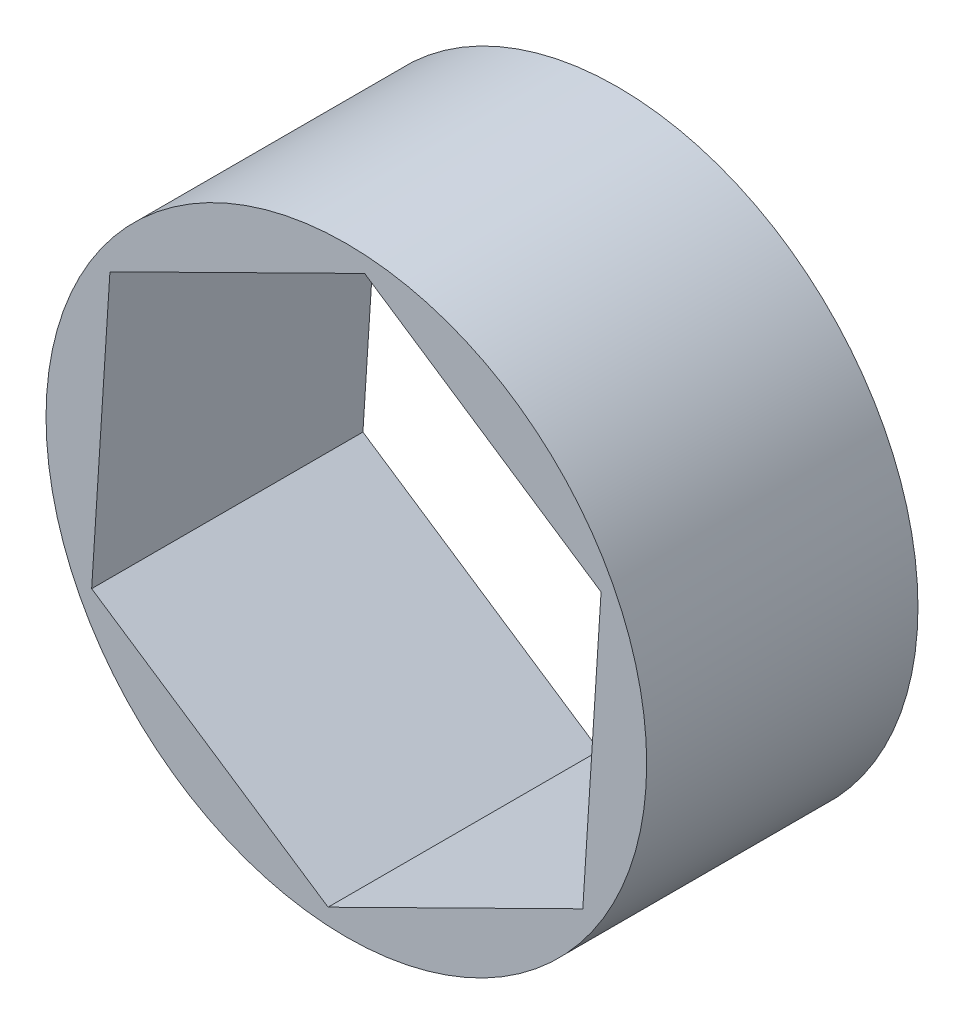
SolidWorks part; units mm, degrees
ref_plane "Front Plane" through (0, 0, 0) normal (0, 0, 1) x (1, 0, 0)
ref_plane "Top Plane" through (0, 0, 0) normal (0, 1, 0) x (1, 0, 0)
ref_plane "Right Plane" through (0, 0, 0) normal (1, 0, 0) x (0, 0, -1)
sketch "Sketch1" plane through (0, 0, 0) normal (0, 0, 1) x (1, 0, 0)
  line L1 (-6.1009, 4.0673) -> (-6.5728, -3.2499)
  line L2 (-6.5728, -3.2499) -> (-0.4719, -7.3171)
  line L3 (-0.4719, -7.3171) -> (6.1009, -4.0673)
  line L4 (6.1009, -4.0673) -> (6.5728, 3.2499)
  line L5 (6.5728, 3.2499) -> (0.4719, 7.3171)
  line L6 (0.4719, 7.3171) -> (-6.1009, 4.0673)
  circle A0 centre (0, 0) radius 6.35 construction
  circle A1 centre (0, 0) radius 7.75
  dimension "D1" = 12.7
  dimension "D2" = 15.5
extrude "Boss-Extrude1" add sketch "Sketch1" along normal blind 7
